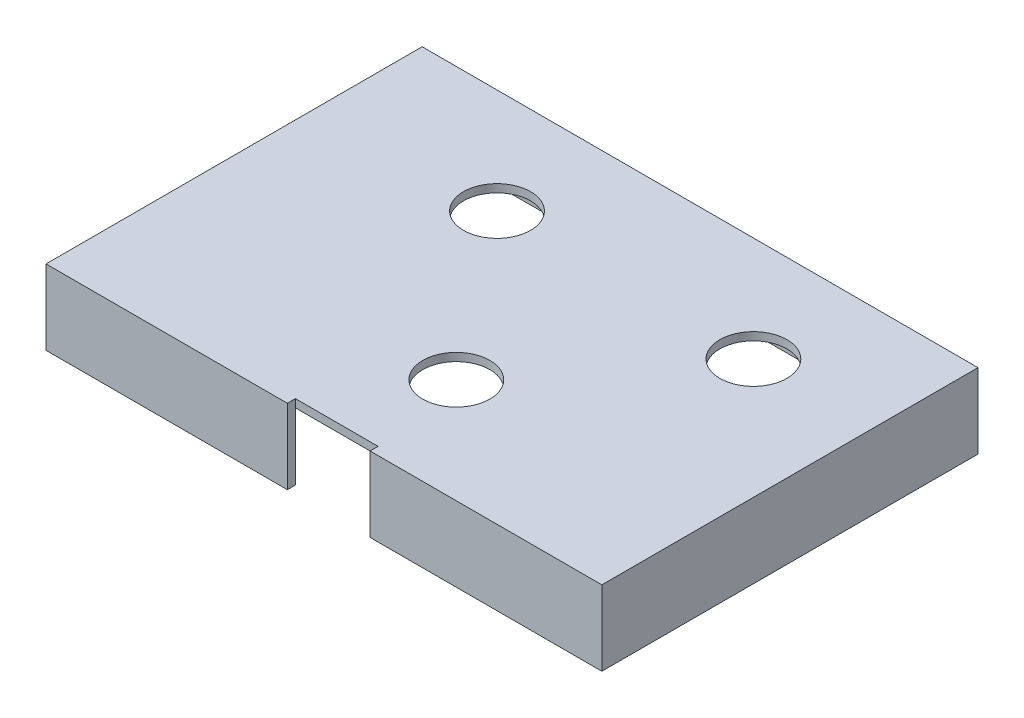
SolidWorks part; units mm, degrees
ref_plane "Front Plane" through (0, 0, 0) normal (0, 0, 1) x (1, 0, 0)
ref_plane "Top Plane" through (0, 0, 0) normal (0, 1, 0) x (1, 0, 0)
ref_plane "Right Plane" through (0, 0, 0) normal (1, 0, 0) x (0, 0, -1)
sketch "Sketch1" plane through (0, 0, 0) normal (0, 1, 0) x (1, 0, 0)
  line L1 (0, 0) -> (235.712, 0)
  line L2 (0, 0) -> (0, 159.512)
  line L3 (0, 159.512) -> (235.712, 159.512)
  line L4 (235.712, 0) -> (235.712, 159.512)
  dimension "D1" = 235.712
  dimension "D2" = 159.512
extrude "Boss-Extrude1" add sketch "Sketch1" along normal blind 31.75
sketch "Sketch2" plane through (0, 0, 0) normal (0, -1, 0) x (1, 0, 0)
  line L0 (0, -159.512) -> (0, 0) construction
  line L1 (3.4036, -3.4036) -> (232.3084, -3.4036)
  line L2 (3.4036, -3.4036) -> (3.4036, -156.1084)
  line L3 (3.4036, -156.1084) -> (232.3084, -156.1084)
  line L4 (232.3084, -3.4036) -> (232.3084, -156.1084)
  line L5 (235.712, 0) -> (235.712, -159.512) construction
  line L6 (0, 0) -> (235.712, 0) construction
  line L7 (235.712, -159.512) -> (0, -159.512) construction
  dimension "D1" = 3.4036
  dimension "D2" = 3.4036
  dimension "D3" = 3.4036
  dimension "D4" = 3.4036
extrude "Cut-Extrude1" cut sketch "Sketch2" against normal blind 28.3464
sketch "Sketch3" plane through (0, 31.75, 0) normal (0, 1, 0) x (1, 0, 0)
  line L0 (0, 159.512) -> (0, 0) construction
  line L1 (0, 0) -> (235.712, 0) construction
  line L2 (102.362, 0) -> (102.362, 3.4036)
  line L3 (102.362, 3.4036) -> (137.414, 3.4036)
  line L4 (137.414, 3.4036) -> (137.414, 0)
  line L7 (102.362, 0) -> (137.414, 0)
  dimension "D1" = 102.362
  dimension "D2" = 35.052
  dimension "D3" = 3.4036
extrude "Cut-Extrude2" cut sketch "Sketch3" against normal through all
sketch "Sketch4" plane through (0, 31.75, 0) normal (0, 1, 0) x (1, 0, 0)
  line L0 (235.712, 159.512) -> (0, 159.512) construction
  line L1 (235.712, 0) -> (235.712, 159.512) construction
  line L2 (0, 0) -> (102.362, 0) construction
  line L3 (0, 159.512) -> (0, 0) construction
  circle A0 centre (76.2, 115.062) radius 14.224
  circle A1 centre (129.54, 44.45) radius 14.224
  circle A2 centre (184.912, 115.062) radius 14.224
  point P6 (187.1498, 110.6151)
  point P7 (110.5033, 53.7987)
  point P8 (47.0026, 118.8591)
  dimension "D1" = 28.448
  dimension "D2" = 28.448
  dimension "D3" = 28.448
  dimension "D4" = 44.45
  dimension "D5" = 50.8
  dimension "D6" = 44.45
  dimension "D7" = 129.54
  dimension "D8" = 44.45
  dimension "D9" = 76.2
extrude "Cut-Extrude3" cut sketch "Sketch4" against normal through all
